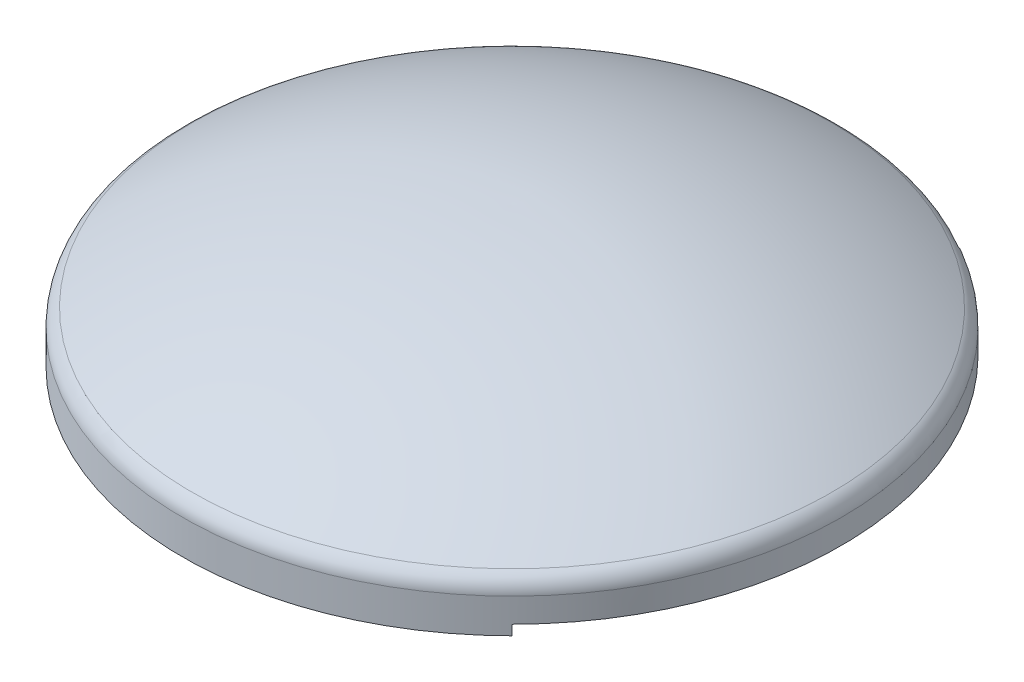
SolidWorks part; units mm, degrees
ref_plane "前视基准面" through (0, 0, 0) normal (0, 0, 1) x (1, 0, 0)
ref_plane "上视基准面" through (0, 0, 0) normal (0, 1, 0) x (1, 0, 0)
ref_plane "右视基准面" through (0, 0, 0) normal (1, 0, 0) x (0, 0, -1)
sketch "Sketch1" plane through (0, 0, 0) normal (1, 0, 0) x (0, 0, -1)
  line L0 (0, 0) -> (30, 0) construction
  line L1 (30, 3.54) -> (10, 3.54) construction
  line L2 (10, 3.54) -> (10, 10.04) construction
  line L3 (10, 10.04) -> (0, 10.04) construction
  line L4 (0, 10.04) -> (0, 0) construction
  line L5 (30, 3.54) -> (30, 0) construction
  line L6 (30, 0) -> (25, 0)
  line L7 (25, 0) -> (25, -1)
  line L8 (25, -1) -> (33, -1)
  line L9 (33, -1) -> (33, 3.54)
  line L10 (30, 0) -> (30.9775, 0)
  line L11 (30.9775, 0) -> (30.9775, 3.5454)
  line L12 (0, -4.6308) -> (0, 9.0048) construction
  line L18 (0, 11.04) -> (0, 13.0214)
  arc A0 (0, 11.04) -> (30.9775, 3.5454) centre (1.8864, -48.9303) cw
  arc A1 (0, 13.0214) -> (33, 3.54) centre (0.6241, -46.9754) cw
  point P8 (33, 3.54)
  point P11 (0, 11.04)
  dimension "D1" = 3.54
  dimension "D2" = 6.5
  dimension "D3" = 30
  dimension "D4" = 10
  dimension "D5" = 1
  dimension "D6" = 5
  dimension "D7" = 1
  dimension "D8" = 3
revolve "Revolve1" add sketch "Sketch1" angle 360 about L18
sketch "Sketch2" plane through (0, 0, 0) normal (1, 0, 0) x (0, 0, -1)
  line L0 (30.9775, 0) -> (25, 0)
  line L1 (25, 0) -> (25, -1)
  line L2 (25, -1) -> (33, -1)
  line L3 (33, -1) -> (33, 0)
  line L4 (33, -1) -> (33, 3.54) construction
  line L5 (33, 0) -> (30.9775, 0)
revolve "Cut-Revolve1" cut sketch "Sketch2" angle 270 mid plane about L4
fillet "Fillet1" radius 2 1 edges at (0, 3.54, -33)
sketch "Sketch3" plane through (0, 0, 0) normal (0, 0, 1) x (1, 0, 0)
  line L0 (0, -7.7237) -> (0, 17.403) construction
  line L1 (-16.5, 0) -> (16.5, 0)
  line L2 (16.5, 0) -> (16.5, 3.55)
  line L3 (16.5, 3.55) -> (-16.5, 3.55)
  line L4 (-16.5, 0) -> (-16.5, 3.55)
  point P8 (0, 0)
  point P9 (0, 3.55)
  dimension "D1" = 16.5
  dimension "D2" = 3.55
extrude "Cut-Extrude1" cut sketch "Sketch3" against normal up to next
